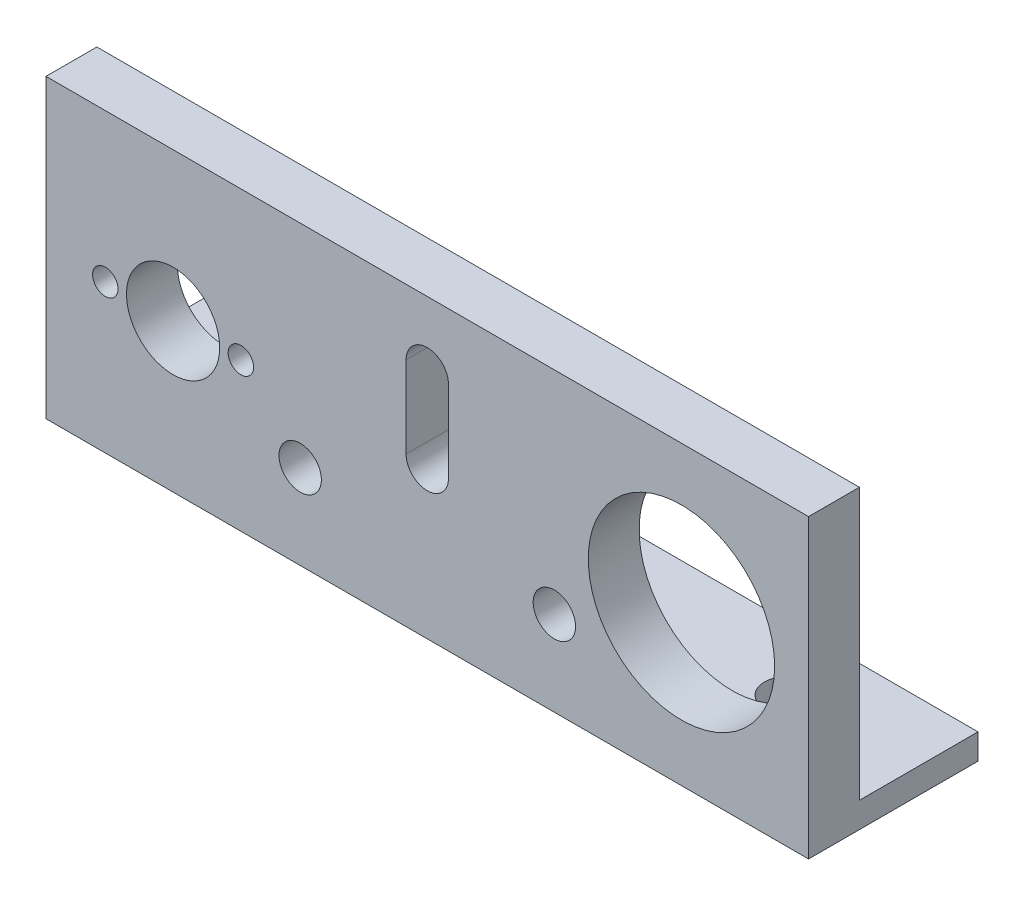
SolidWorks part; units mm, degrees
ref_plane "Front Plane" through (0, 0, 0) normal (0, 0, 1) x (1, 0, 0)
ref_plane "Top Plane" through (0, 0, 0) normal (0, 1, 0) x (1, 0, 0)
ref_plane "Right Plane" through (0, 0, 0) normal (1, 0, 0) x (0, 0, -1)
sketch "Sketch1" plane through (0, 0, 0) normal (0, 0, 1) x (1, 0, 0)
  line L1 (-45, -17.5) -> (45, -17.5)
  line L2 (-45, -17.5) -> (-45, 17.5)
  line L3 (-45, 17.5) -> (45, 17.5)
  line L4 (45, -17.5) -> (45, 17.5)
  line L5 (-45, -17.5) -> (45, 17.5) construction
  line L6 (-45, 17.5) -> (45, -17.5) construction
  circle A0 centre (-30, 0) radius 5.5
  circle A1 centre (-38, 0) radius 1.5
  circle A2 centre (-22, 0) radius 1.5
  circle A3 centre (29.9997, 0.2) radius 11
  point P0 (0, 0)
  point P14 (0, 0)
  dimension "D3" = 11
  dimension "D4" = 3
  dimension "D5" = 3
  dimension "D11" = 22
  dimension "D1" = 90
  dimension "D2" = 35
  dimension "D6" = 16
  dimension "D7" = 8
  dimension "D8" = 17.5
  dimension "D9" = 60
  dimension "D10" = 15
  dimension "D12" = 17.3
extrude "Boss-Extrude1" add sketch "Sketch1" along normal blind 6
sketch "Sketch2" plane through (0, 0, 6) normal (0, 0, 1) x (1, 0, 0)
  line L0 (45, -17.5) -> (45, 17.5) construction
  line L1 (-45, -17.5) -> (45, -17.5)
  line L2 (-45, -17.5) -> (-45, -14.5)
  line L3 (-45, -14.5) -> (45, -14.5)
  line L4 (45, -17.5) -> (45, -14.5)
  dimension "D1" = 3
extrude "Boss-Extrude2" add sketch "Sketch2" against normal blind 20
sketch "Sketch4" plane through (0, 0, 6) normal (0, 0, 1) x (1, 0, 0)
  line L0 (0, 35.5343) -> (0, -35.2513) construction
  line L1 (0, 9.779) -> (0, 0.1415) construction
  line L2 (2.5, 9.779) -> (2.5, 0.1415)
  line L3 (-2.5, 9.779) -> (-2.5, 0.1415)
  line L5 (45, 17.5) -> (-45, 17.5) construction
  circle A0 centre (15, -7.5) radius 2.5
  arc A2 (2.5, 9.779) -> (-2.5, 9.779) centre (0, 9.779) ccw
  arc A3 (-2.5, 0.1415) -> (2.5, 0.1415) centre (0, 0.1415) ccw
  circle A4 centre (-15, -7.5) radius 2.5
  point P8 (0, 4.9603)
  dimension "D1" = 15
  dimension "D2" = 5
  dimension "D3" = 2.5
  dimension "D5" = 25
extrude "Cut-Extrude1" cut sketch "Sketch4" against normal blind 10
sketch "Sketch5" plane through (0, -14.5, 0) normal (0, 1, 0) x (1, 0, 0)
  line L0 (45, 14) -> (45, 0) construction
  line L1 (45, 14) -> (-45, 14) construction
  line L2 (0, 41.8575) -> (0, -20.6725) construction
  circle A0 centre (30, 6.5) radius 2.7
  circle A2 centre (-30, 6.5) radius 2.7
  dimension "D3" = 5.4
  dimension "D1" = 15
  dimension "D2" = 7.5
extrude "Cut-Extrude2" cut sketch "Sketch5" against normal blind 10
